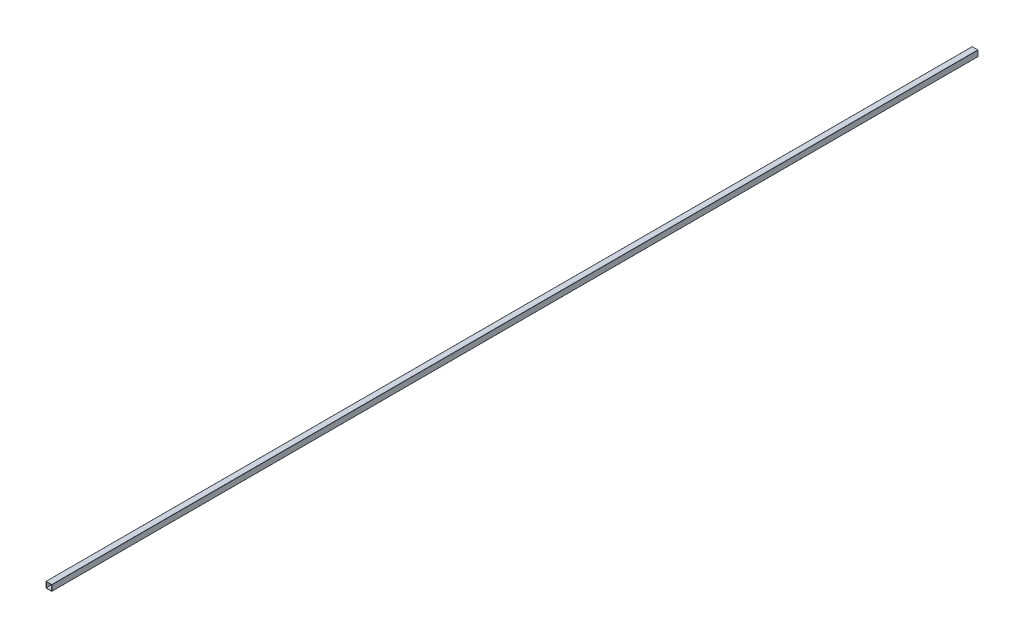
SolidWorks part; units mm, degrees
material "AISI 1035 Acero (SS)"
ref_plane "Alzado" through (0, 0, 0) normal (0, 0, 1) x (1, 0, 0)
ref_plane "Planta" through (0, 0, 0) normal (0, 1, 0) x (1, 0, 0)
ref_plane "Vista lateral" through (0, 0, 0) normal (1, 0, 0) x (0, 0, -1)
sketch "Croquis1" plane through (0, 0, 0) normal (0, 0, 1) x (1, 0, 0)
  line L0 (-17.16, -17.16) -> (-17.16, 17.16)
  line L1 (-18.05, -19.05) -> (18.05, -19.05)
  line L2 (-19.05, -18.05) -> (-19.05, 18.05)
  line L3 (-18.05, 19.05) -> (18.05, 19.05)
  line L4 (19.05, -18.05) -> (19.05, 18.05)
  line L5 (-19.05, -19.05) -> (19.05, 19.05) construction
  line L6 (-19.05, 19.05) -> (19.05, -19.05) construction
  line L7 (-17.16, 17.16) -> (17.16, 17.16)
  line L8 (17.16, -17.16) -> (17.16, 17.16)
  line L9 (-17.16, -17.16) -> (17.16, -17.16)
  line L10 (-19.05, 19.05) -> (19.05, 19.05) construction
  line L11 (19.05, -19.05) -> (19.05, 19.05) construction
  line L12 (-19.05, -19.05) -> (19.05, -19.05) construction
  line L13 (-19.05, -19.05) -> (-19.05, 19.05) construction
  arc A0 (18.05, 19.05) -> (19.05, 18.05) centre (18.05, 18.05) cw
  arc A1 (18.05, -19.05) -> (19.05, -18.05) centre (18.05, -18.05) ccw
  arc A2 (-18.05, -19.05) -> (-19.05, -18.05) centre (-18.05, -18.05) cw
  arc A3 (-19.05, 18.05) -> (-18.05, 19.05) centre (-18.05, 18.05) cw
  point P0 (0, 0)
  dimension "D2" = 1
  dimension "D1" = 38.1
  dimension "D3" = 1.89
extrude "Saliente-Extruir1" add sketch "Croquis1" along normal blind 6000
